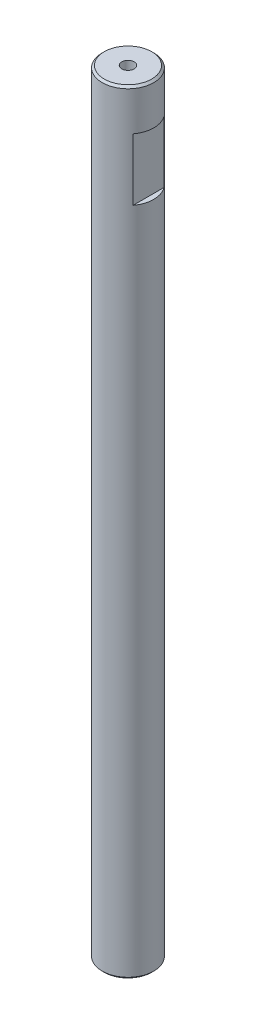
SolidWorks part; units mm, degrees
ref_plane "前视基准面" through (0, 0, 0) normal (0, 0, 1) x (1, 0, 0)
ref_plane "上视基准面" through (0, 0, 0) normal (0, 1, 0) x (1, 0, 0)
ref_plane "右视基准面" through (0, 0, 0) normal (1, 0, 0) x (0, 0, -1)
other "Configuration Table"
sketch "草图2" plane through (0, 0, 0) normal (0, 1, 0) x (1, 0, 0)
  circle A0 centre (0, 0) radius 12.5
extrude "凸台-拉伸3" add sketch "草图2" along normal blind 375
sketch "草图5" plane through (0, 0, 0) normal (0, -1, 0) x (1, 0, 0)
  circle A0 centre (0, 0) radius 3
extrude "切除-拉伸2" cut sketch "草图5" against normal blind 20
cosmetic thread "装饰螺纹线2" parameters "D2"=8
sketch "草图7" plane through (0, 375, 0) normal (0, 1, 0) x (1, 0, 0)
  line L1 (10, 0) -> (10, 7.5)
  line L2 (10, 0) -> (10, -7.5)
  line L4 (-10, 0) -> (-10, -7.5)
  line L5 (-10, 0) -> (-10, 7.5)
  circle A0 centre (0, 0) radius 12.5 construction
  circle A1 centre (0, 0) radius 12.5
  circle M6 centre (0, 0) radius 12.5
extrude "切除-拉伸3" cut sketch "草图7" against normal blind 50 contours L1 L2 M6 | L4 L5 M6
sketch "草图11" plane through (0, 375, 0) normal (0, 1, 0) x (1, 0, 0)
  circle A0 centre (0, 0) radius 12.5
  circle A1 centre (0, 0) radius 3
extrude "凸台-拉伸5" add sketch "草图11" against normal blind 20 contours A0
sketch "草图12" plane through (0, 375, 0) normal (0, 1, 0) x (1, 0, 0)
  circle A0 centre (0, 0) radius 3
extrude "切除-拉伸4" cut sketch "草图12" against normal blind 20
cosmetic thread "装饰螺纹线1" parameters "D2"=8
chamfer "倒角1" distance 1 angle 45 1 edges at (0, 0, 12.5)
chamfer "倒角2" distance 1 angle 45 1 edges at (0, 375, 12.5)
